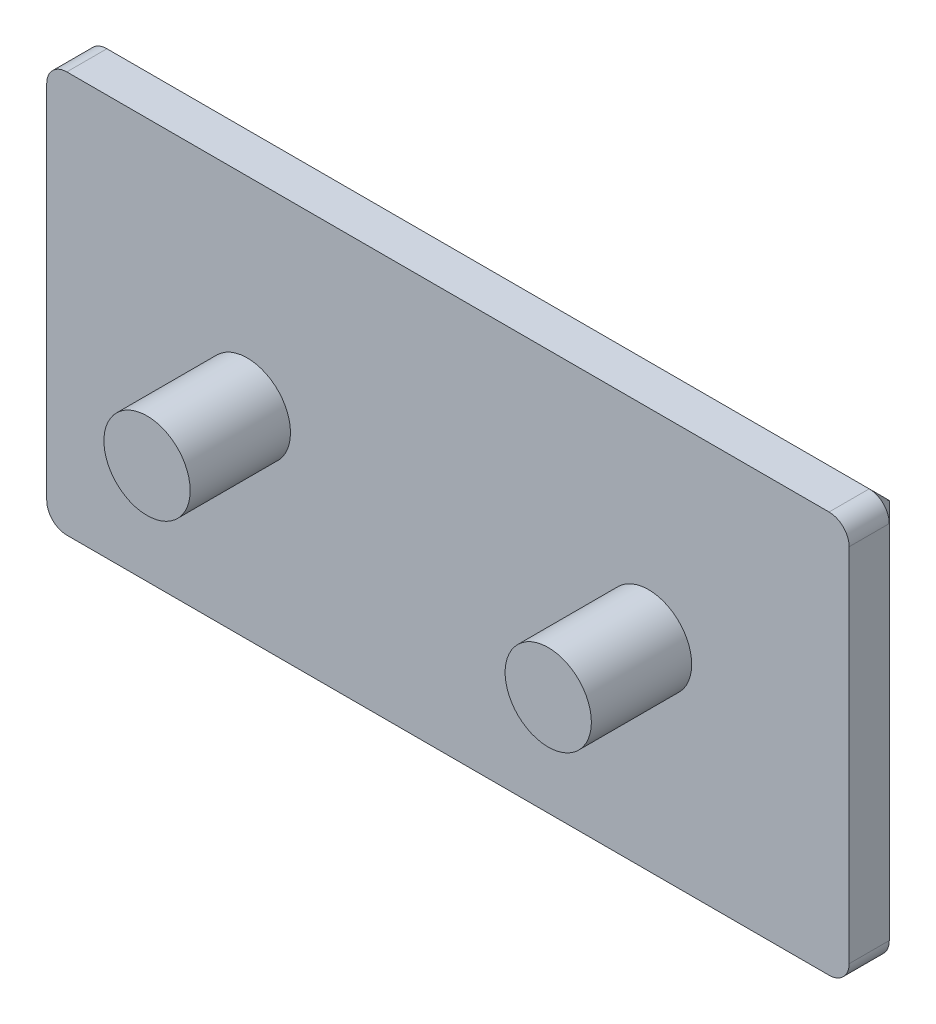
SolidWorks part; units mm, degrees
ref_plane "Front Plane" through (0, 0, 0) normal (0, 0, 1) x (1, 0, 0)
ref_plane "Top Plane" through (0, 0, 0) normal (0, 1, 0) x (1, 0, 0)
ref_plane "Right Plane" through (0, 0, 0) normal (1, 0, 0) x (0, 0, -1)
sketch "Sketch1" plane through (0, 0, 0) normal (0, 0, 1) x (1, 0, 0)
  line L1 (-20, 10) -> (20, 10)
  line L2 (-20, 10) -> (-20, -10)
  line L3 (-20, -10) -> (20, -10)
  line L4 (20, 10) -> (20, -10)
  line L5 (-20, 10) -> (20, -10) construction
  line L6 (-20, -10) -> (20, 10) construction
  point P0 (0, 0)
  dimension "D1" = 40
  dimension "D2" = 20
extrude "Boss-Extrude1" add sketch "Sketch1" along normal blind 3
sketch "Sketch2" plane through (0, 0, 3) normal (0, 0, 1) x (1, 0, 0)
  line L0 (0, 0) -> (0, -16.8748) construction
  circle A0 centre (10, 0) radius 2.15
  circle A1 centre (-10, 0) radius 2.15
  point P4 (0, 0)
  dimension "D1" = 4.3
  dimension "D2" = 20
extrude "Boss-Extrude2" add sketch "Sketch2" along normal blind 5
fillet "Fillet1" radius 1 4 edges at (20, -10, 1.5) (-20, -10, 1.5) (20, 10, 1.5) (-20, 10, 1.5)
chamfer "Chamfer1" distance 1 angle 45 8 edges at (19.7071, 9.7071, 0) (0, 10, 0) (-19.7071, 9.7071, 0) (-20, 0, 0) (-19.7071, -9.7071, 0) (0, -10, 0) (19.7071, -9.7071, 0) (20, 0, 0)
